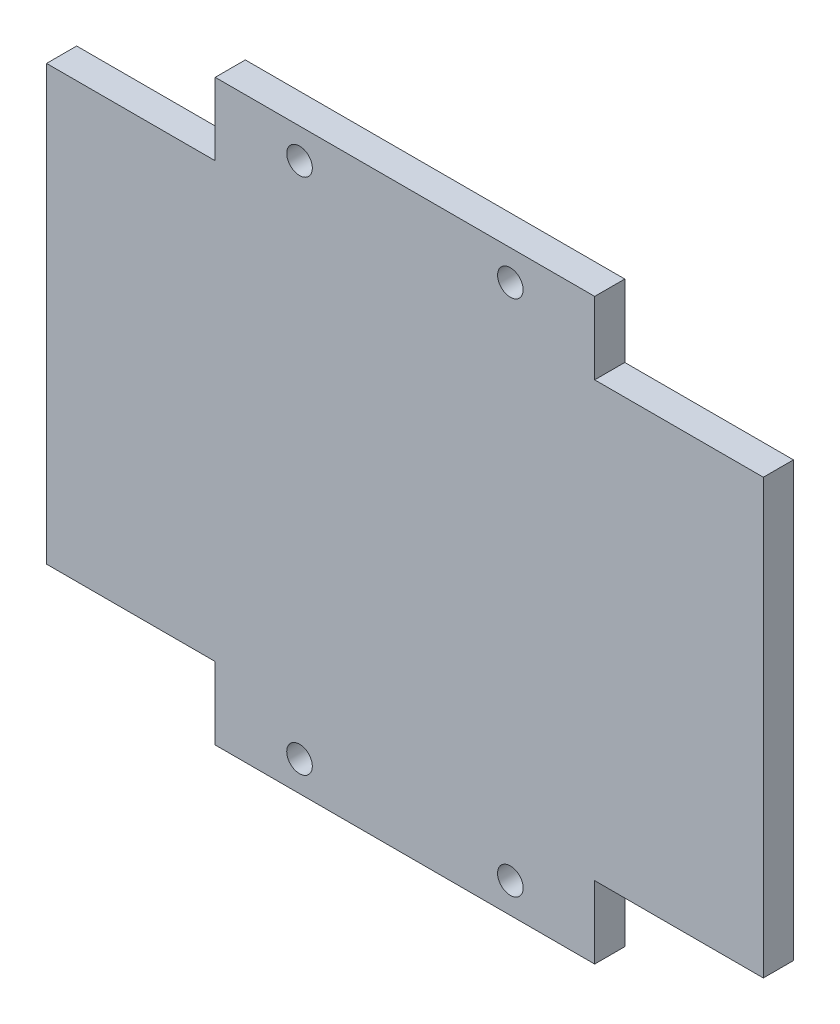
SolidWorks part; units mm, degrees
ref_plane "Front Plane" through (0, 0, 0) normal (0, 0, 1) x (1, 0, 0)
ref_plane "Top Plane" through (0, 0, 0) normal (0, 1, 0) x (1, 0, 0)
ref_plane "Right Plane" through (0, 0, 0) normal (1, 0, 0) x (0, 0, -1)
sketch "Sketch2" plane through (0, 0, 0) normal (0, 0, 1) x (1, 0, 0)
  line L1 (0, 0) -> (63, 0)
  line L2 (0, 0) -> (0, 96)
  line L3 (0, 96) -> (63, 96)
  line L4 (63, 0) -> (63, 96)
  dimension "D1" = 96
  dimension "D2" = 63
extrude "Boss-Extrude1" add sketch "Sketch2" along normal blind 5
sketch "Sketch3" plane through (0, 0, 5) normal (0, 0, 1) x (1, 0, 0)
  line L0 (63, 96) -> (0, 96) construction
  line L1 (0, 96) -> (0, 0) construction
  line L2 (31.5, 66.7376) -> (31.5, 29.4197) construction
  line L3 (19.4472, 48) -> (50.0643, 48) construction
  line L4 (63, 0) -> (63, 96) construction
  circle A0 centre (14, 91) radius 2.125
  circle A2 centre (49, 91) radius 2.125
  circle A3 centre (49, 5) radius 2.125
  circle A4 centre (14, 5) radius 2.125
  dimension "D1" = 4.25
  dimension "D2" = 5
  dimension "D3" = 14
  dimension "D4" = 48
  dimension "D5" = 31.5
extrude "Cut-Extrude1" cut sketch "Sketch3" against normal blind 5
sketch "Sketch4" plane through (0, 0, 5) normal (0, 0, 1) x (1, 0, 0)
  line L0 (63, 0) -> (63, 96) construction
  line L1 (63, 84) -> (91, 84)
  line L2 (63, 84) -> (63, 12)
  line L3 (63, 12) -> (91, 12)
  line L4 (91, 84) -> (91, 12)
  line L5 (0, 96) -> (0, 0) construction
  line L6 (0, 84) -> (-28, 84)
  line L7 (0, 84) -> (0, 12)
  line L8 (0, 12) -> (-28, 12)
  line L9 (-28, 84) -> (-28, 12)
  line L10 (63, 96) -> (0, 96) construction
  line L11 (0, 0) -> (63, 0) construction
  dimension "D1" = 12
  dimension "D2" = 12
  dimension "D3" = 28
  dimension "D4" = 28
  dimension "D5" = 12
  dimension "D6" = 12
extrude "Boss-Extrude2" add sketch "Sketch4" against normal blind 5
